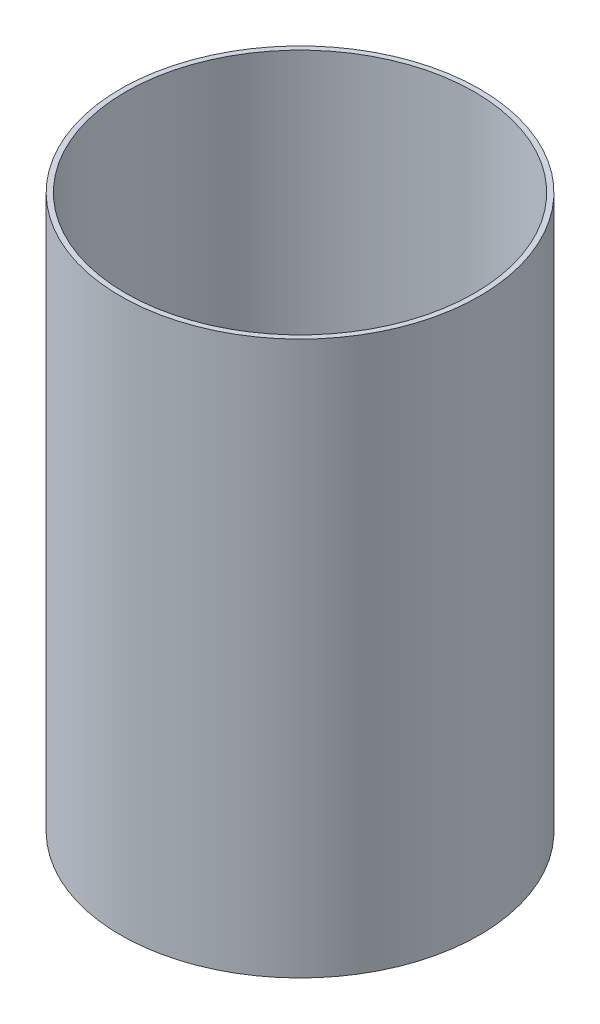
SolidWorks part; units mm, degrees
material "6061-T6 (SS)"
ref_plane "Front Plane" through (0, 0, 0) normal (0, 0, 1) x (1, 0, 0)
ref_plane "Top Plane" through (0, 0, 0) normal (0, 1, 0) x (1, 0, 0)
ref_plane "Right Plane" through (0, 0, 0) normal (1, 0, 0) x (0, 0, -1)
sketch "Sketch1" plane through (0, 0, 0) normal (0, 1, 0) x (1, 0, 0)
  circle A0 centre (0, 0) radius 49.4538
  circle A1 centre (0, 0) radius 48.0441
  dimension "D1" = 98.9076
  dimension "D2" = 96.0882
extrude "Boss-Extrude1" add sketch "Sketch1" along normal blind 152.4
equation "\"CF_OD_A\"= 4.015in"
equation "\"CF_ID_A\"= 3.904in"
equation "\"KF_ID_A\"= 4.015in ' Kevlar airframe ID"
equation "\"CD_OD_C\"= 3.894in ' VERIFY Coupler OD"
equation "\"CF_ID_C\"= 3.783in ' VERIFY Coupler ID"
equation "\"KF_WALL\"= 0.0625in"
equation "\"AF_01\"=10in"
equation "\"AF_02\"=16in"
equation "\"AF_03\"=in"
equation "\"D1@Sketch1\"=\"CD_OD_C\""
equation "\"D2@Sketch1\"=\"CF_ID_C\""
